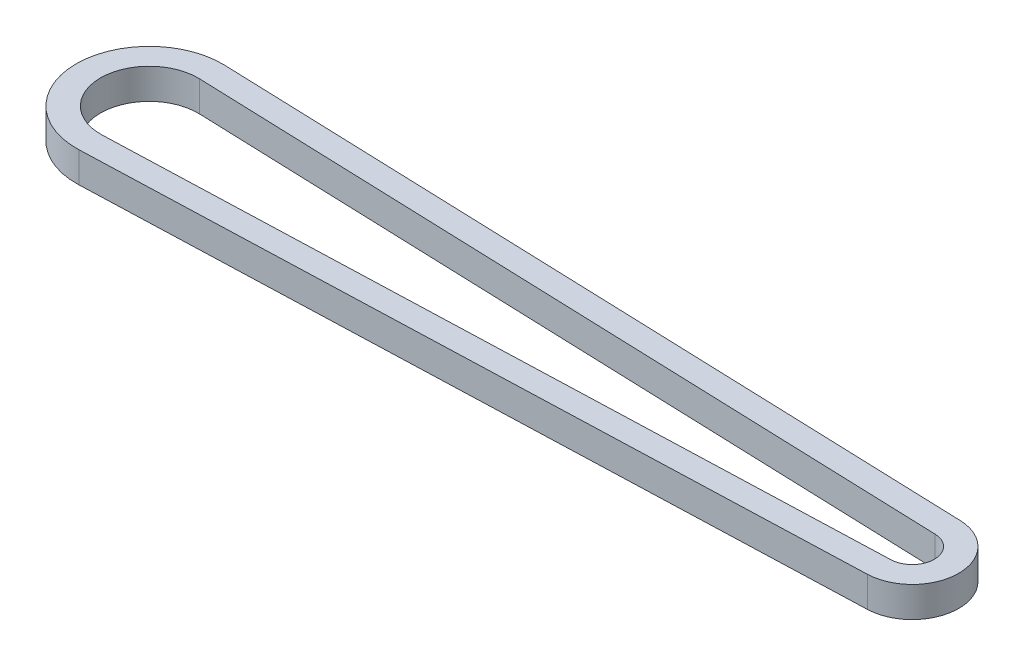
SolidWorks part; units mm, degrees
ref_plane "Front Plane" through (0, 0, 0) normal (0, 0, 1) x (1, 0, 0)
ref_plane "Top Plane" through (0, 0, 0) normal (0, 1, 0) x (1, 0, 0)
ref_plane "Right Plane" through (0, 0, 0) normal (1, 0, 0) x (0, 0, -1)
sketch "Sketch1" plane through (0, 0, 0) normal (0, 1, 0) x (1, 0, 0)
  line L0 (0.6966, 19.9879) -> (313.5166, 9.0854)
  line L2 (313.5166, -9.0854) -> (0.6966, -19.9879)
  arc A0 (0.6966, 19.9879) -> (0.6966, -19.9879) centre (0, 0) ccw
  arc A1 (313.5166, -9.0854) -> (313.5166, 9.0854) centre (313.2, 0) ccw
  dimension "D1" = 9.0909
  dimension "D2" = 20
  dimension "D3" = 313.2
extrude "Extrude-Thin1" add sketch "Sketch1" along normal blind 12.5 thin thin type one direction wall 10
move or copy body "Body-Move/Copy1" [suppressed] bodies to move or copy 101
equation "\"12.5mmm\"=10"
